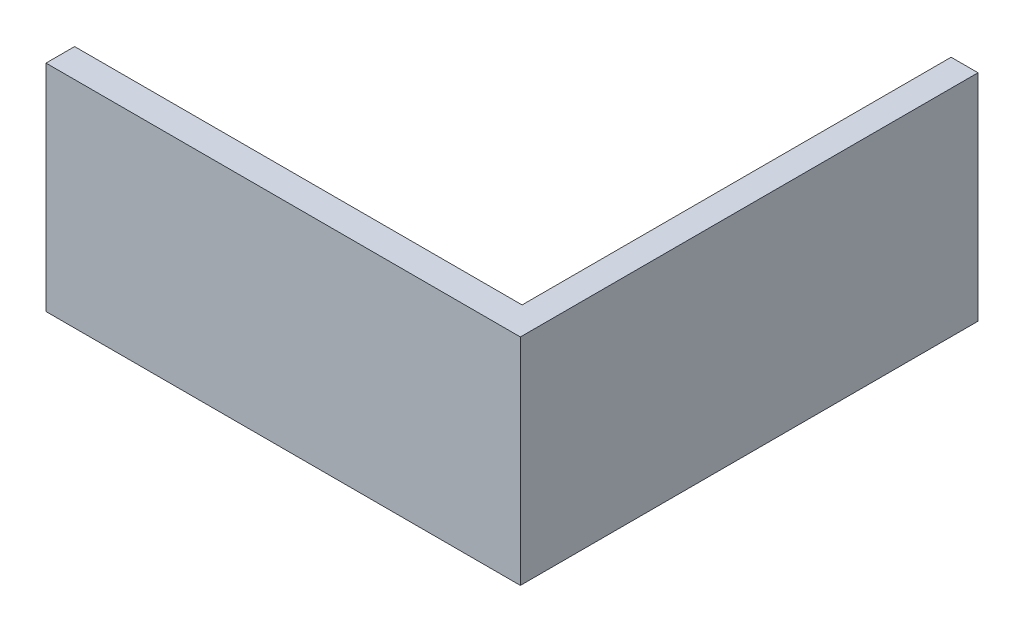
SolidWorks part; units mm, degrees
ref_plane "Front Plane" through (0, 0, 0) normal (0, 0, 1) x (1, 0, 0)
ref_plane "Top Plane" through (0, 0, 0) normal (0, 1, 0) x (1, 0, 0)
ref_plane "Right Plane" through (0, 0, 0) normal (1, 0, 0) x (0, 0, -1)
sketch "Sketch1" plane through (0, 0, 0) normal (0, 0, 1) x (1, 0, 0)
  line L1 (-82.9294, 37.6215) -> (82.9294, 37.6215)
  line L2 (-82.9294, 37.6215) -> (-82.9294, -37.6215)
  line L3 (-82.9294, -37.6215) -> (82.9294, -37.6215)
  line L4 (82.9294, 37.6215) -> (82.9294, -37.6215)
  line L5 (-82.9294, 37.6215) -> (82.9294, -37.6215) construction
  line L6 (-82.9294, -37.6215) -> (82.9294, 37.6215) construction
  point P0 (0, 0)
extrude "Boss-Extrude1" add sketch "Sketch1" along normal blind 10
sketch "Sketch2" plane through (0, 0, 0) normal (0, 0, 1) x (1, 0, 0)
  line L0 (82.9294, 37.6215) -> (-82.9294, 37.6215) construction
  line L1 (73.5306, 37.6215) -> (82.9294, 37.6215)
  line L2 (73.5306, 37.6215) -> (73.5306, -37.6215)
  line L3 (73.5306, -37.6215) -> (82.9294, -37.6215)
  line L4 (82.9294, 37.6215) -> (82.9294, -37.6215)
extrude "Boss-Extrude2" add sketch "Sketch2" against normal blind 150
sketch "Sketch4" plane through (0, 0, 0) normal (0, 0, 1) x (1, 0, 0)
  line L0 (73.5306, 37.6215) -> (73.5306, -37.6215) construction
  circle A0 centre (-16.4694, 0) radius 5
  dimension "D1" = 10
  dimension "D2" = 90
extrude "Boss-Extrude3" add sketch "Sketch4" against normal blind 30 separate body
sketch "Sketch5" plane through (73.5306, 0, 0) normal (-1, 0, 0) x (0, 0, 1)
  line L0 (0, 37.6215) -> (0, -37.6215) construction
  circle A0 centre (-90, 0) radius 5
  dimension "D1" = 10
  dimension "D2" = 90
extrude "Boss-Extrude4" add sketch "Sketch5" along normal blind 30
